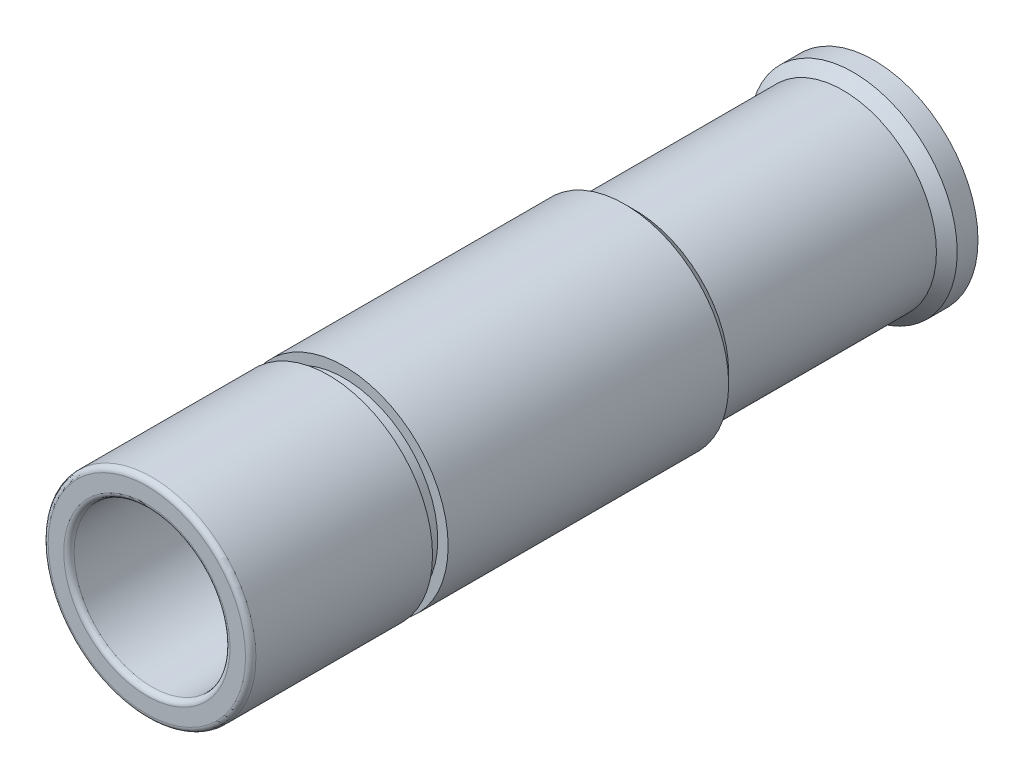
SolidWorks part; units mm, degrees
material "Сталь 20 ГОСТ 1050-88"
ref_plane "Спереди" through (0, 0, 0) normal (0, 0, 1) x (1, 0, 0)
ref_plane "Сверху" through (0, 0, 0) normal (0, 1, 0) x (1, 0, 0)
ref_plane "Справа" through (0, 0, 0) normal (1, 0, 0) x (0, 0, -1)
sketch "Эскиз1" plane through (0, 0, 0) normal (1, 0, 0) x (0, 0, -1)
  line L0 (23, 0) -> (35, 0)
  line L1 (0, 3.75) -> (0, 5)
  line L2 (23, 5) -> (23.5, 4.5)
  line L4 (23, 5) -> (9.5, 5)
  line L6 (35, 5) -> (35, 0)
  line L7 (35, 5) -> (34, 5)
  line L8 (34, 5) -> (33.5, 4.5)
  line L12 (8.75, 4.5) -> (9.5, 4.5)
  line L13 (9.5, 4.5) -> (9.5, 5)
  line L14 (0, 5) -> (8.75, 5)
  line L15 (8.75, 4.5) -> (8.75, 5)
  line L16 (23, 3.75) -> (0, 3.75)
  line L17 (23, 3.75) -> (23, 0)
  line L19 (23.5, 4.5) -> (33.5, 4.5)
revolve "Повернуть1" add sketch "Эскиз1" angle 360 about L0
fillet "Скругление1" radius 0.25 2 edges at (3.75, 0, 0) (5, 0, 0)
